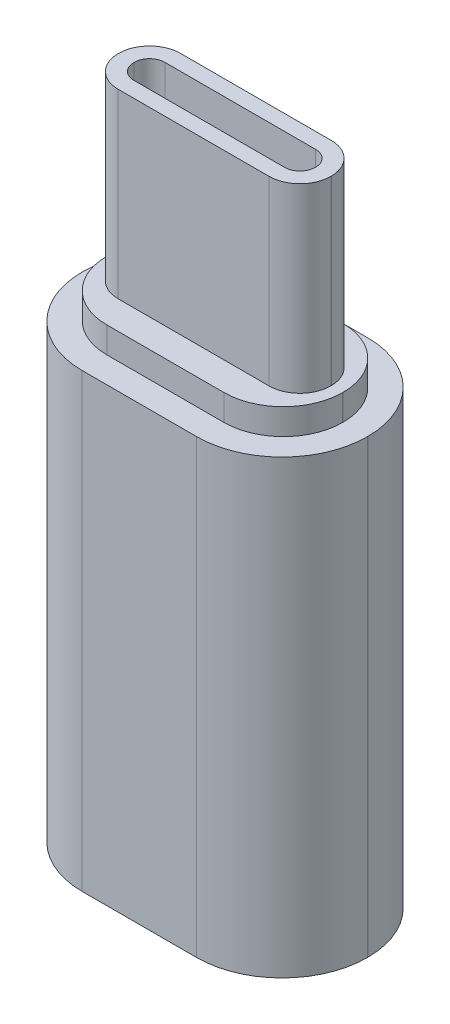
SolidWorks part; units mm, degrees
ref_plane "Front Plane" through (0, 0, 0) normal (0, 0, 1) x (1, 0, 0)
ref_plane "Top Plane" through (0, 0, 0) normal (0, 1, 0) x (1, 0, 0)
ref_plane "Right Plane" through (0, 0, 0) normal (1, 0, 0) x (0, 0, -1)
sketch "Sketch1" plane through (0, 0, 0) normal (0, 1, 0) x (1, 0, 0)
  line L1 (3.29, 0) -> (7.71, 0)
  line L2 (0, 3.29) -> (0, 3.31)
  line L3 (3.29, 6.6) -> (7.71, 6.6)
  line L4 (11, 3.29) -> (11, 3.31)
  arc A0 (7.71, 6.6) -> (11, 3.31) centre (7.71, 3.31) cw
  arc A1 (11, 3.29) -> (7.71, 0) centre (7.71, 3.29) cw
  arc A2 (3.29, 0) -> (0, 3.29) centre (3.29, 3.29) cw
  arc A3 (0, 3.31) -> (3.29, 6.6) centre (3.29, 3.31) cw
  point P9 (11, 0)
  point P12 (0, 0)
  point P15 (0, 6.6)
  dimension "D3" = 3.29
  dimension "D1" = 6.6
  dimension "D2" = 11
extrude "Boss-Extrude1" add sketch "Sketch1" along normal blind 17.4
sketch "Sketch2" plane through (0, 17.4, 0) normal (0, 1, 0) x (1, 0, 0)
  line L0 (0, 3.31) -> (11, 3.29) construction
  line L1 (3.24, 1) -> (7.76, 1)
  line L2 (0.95, 3.29) -> (0.95, 3.31)
  line L3 (3.24, 5.6) -> (7.76, 5.6)
  line L4 (10.05, 3.29) -> (10.05, 3.31)
  line L5 (0.95, 5.6) -> (10.05, 1) construction
  line L6 (0.95, 1) -> (10.05, 5.6) construction
  arc A0 (7.76, 5.6) -> (10.05, 3.31) centre (7.76, 3.31) cw
  arc A1 (10.05, 3.29) -> (7.76, 1) centre (7.76, 3.29) cw
  arc A2 (3.24, 1) -> (0.95, 3.29) centre (3.24, 3.29) cw
  arc A3 (0.95, 3.31) -> (3.24, 5.6) centre (3.24, 3.31) cw
  point P8 (5.5, 3.3)
  dimension "D3" = 2.29
  dimension "D1" = 9.1
  dimension "D2" = 4.6
extrude "Boss-Extrude2" add sketch "Sketch2" along normal blind 1
sketch "Sketch3" plane through (0, 18.4, 0) normal (0, 1, 0) x (1, 0, 0)
  line L0 (0.95, 3.29) -> (10.05, 3.29) construction
  line L1 (2.59, 2.09) -> (8.41, 2.09)
  line L2 (1.4, 3.28) -> (1.4, 3.3)
  line L3 (2.59, 4.49) -> (8.41, 4.49)
  line L4 (9.6, 3.28) -> (9.6, 3.3)
  line L5 (1.4, 2.09) -> (9.6, 4.49) construction
  line L6 (1.4, 4.49) -> (9.6, 2.09) construction
  arc A0 (9.6, 3.28) -> (8.41, 2.09) centre (8.41, 3.28) cw
  arc A1 (9.6, 3.3) -> (8.41, 4.49) centre (8.41, 3.3) ccw
  arc A2 (2.59, 2.09) -> (1.4, 3.28) centre (2.59, 3.28) cw
  arc A3 (1.4, 3.3) -> (2.59, 4.49) centre (2.59, 3.3) cw
  point P8 (5.5, 3.29)
  point P9 (5.5, 3.29)
  dimension "D3" = 1.19
  dimension "D1" = 2.4
  dimension "D2" = 8.2
extrude "Boss-Extrude3" add sketch "Sketch3" along normal blind 7
sketch "Sketch4" plane through (0, 25.4, 0) normal (0, 1, 0) x (1, 0, 0)
  line L0 (2.59, 4.49) -> (8.41, 4.49) construction
  line L1 (8.41, 2.09) -> (2.59, 2.09) construction
  line L2 (2.59, 3.89) -> (8.41, 3.89)
  line L3 (8.41, 2.69) -> (2.59, 2.69)
  arc A0 (8.41, 4.49) -> (9.6, 3.3) centre (8.41, 3.3) cw construction
  arc A1 (9.6, 3.3) -> (8.41, 2.09) centre (8.41, 3.2802) cw construction
  arc A2 (2.59, 2.09) -> (1.4, 3.28) centre (2.59, 3.28) cw construction
  arc A3 (1.4, 3.28) -> (2.59, 4.49) centre (2.59, 3.2998) cw construction
  arc A4 (2, 3.285) -> (2.59, 3.89) centre (2.59, 3.2998) cw
  arc A5 (8.41, 3.89) -> (9, 3.295) centre (8.41, 3.3) cw
  arc A6 (9, 3.295) -> (8.41, 2.69) centre (8.41, 3.2802) cw
  arc A7 (2.59, 2.69) -> (2, 3.285) centre (2.59, 3.28) cw
  dimension "D1" = 0.6
  dimension "D2" = 1.2
  dimension "D3" = 7
extrude "Cut-Extrude1" cut sketch "Sketch4" against normal blind 4
sketch "Sketch5" plane through (0, 0, 0) normal (0, -1, 0) x (1, 0, 0)
  line L0 (0, -3.29) -> (11, -3.31) construction
  line L1 (1.35, -1.85) -> (9.65, -4.75) construction
  line L2 (2.55, -4.75) -> (8.45, -4.75)
  line L3 (1.35, -3.55) -> (1.35, -3.05)
  line L4 (2.55, -1.85) -> (8.45, -1.85)
  line L5 (9.65, -3.55) -> (9.65, -3.05)
  line L6 (1.35, -4.75) -> (9.65, -1.85) construction
  arc A0 (8.45, -1.85) -> (9.65, -3.05) centre (8.45, -3.05) cw
  arc A1 (9.65, -3.55) -> (8.45, -4.75) centre (8.45, -3.55) cw
  arc A2 (2.55, -4.75) -> (1.35, -3.55) centre (2.55, -3.55) cw
  arc A3 (2.55, -1.85) -> (1.35, -3.05) centre (2.55, -3.05) ccw
  point P8 (5.5, -3.3)
  point P9 (5.5, -3.3)
  dimension "D3" = 1.2
  dimension "D1" = 8.3
  dimension "D2" = 2.9
extrude "Cut-Extrude2" cut sketch "Sketch5" against normal blind 6.5
sketch "Sketch6" plane through (0, 6.5, 0) normal (0, -1, 0) x (1, 0, 0)
  line L0 (1.35, -3.3) -> (9.65, -3.3) construction
  line L1 (1.35, -3.05) -> (1.35, -3.55) construction
  line L2 (9.65, -3.55) -> (9.65, -3.05) construction
  line L3 (2.05, -2.75) -> (8.95, -3.85) construction
  line L4 (2.59, -3.85) -> (8.41, -3.85)
  line L5 (2.05, -3.31) -> (2.05, -3.29)
  line L6 (2.59, -2.75) -> (8.41, -2.75)
  line L7 (8.95, -3.31) -> (8.95, -3.29)
  line L8 (2.05, -3.85) -> (8.95, -2.75) construction
  arc A0 (8.95, -3.29) -> (8.41, -2.75) centre (8.41, -3.29) ccw
  arc A1 (8.95, -3.31) -> (8.41, -3.85) centre (8.41, -3.31) cw
  arc A2 (2.59, -3.85) -> (2.05, -3.31) centre (2.59, -3.31) cw
  arc A3 (2.05, -3.29) -> (2.59, -2.75) centre (2.59, -3.29) cw
  point P10 (5.5, -3.3)
  point P11 (5.5, -3.3)
  dimension "D3" = 0.54
  dimension "D1" = 1.1
  dimension "D2" = 6.9
extrude "Boss-Extrude4" add sketch "Sketch6" along normal blind 2.1
